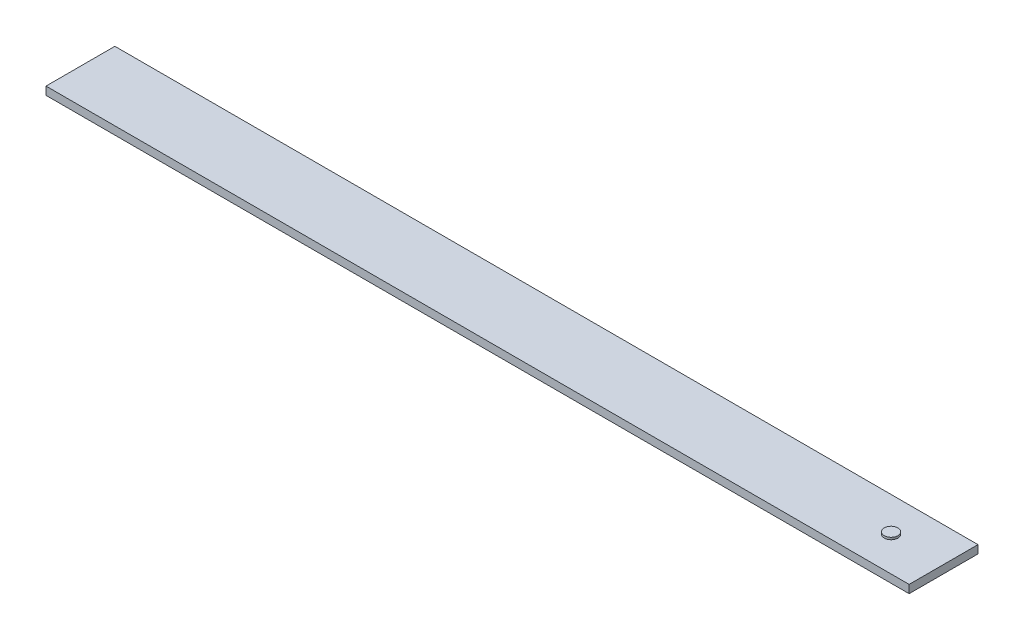
SolidWorks part; units mm, degrees
ref_plane "Plano frontal" through (0, 0, 0) normal (0, 0, 1) x (1, 0, 0)
ref_plane "Plano superior" through (0, 0, 0) normal (0, 1, 0) x (1, 0, 0)
ref_plane "Plano direito" through (0, 0, 0) normal (1, 0, 0) x (0, 0, -1)
sketch "Esboço1" plane through (0, 0, 0) normal (0, 1, 0) x (1, 0, 0)
  line L1 (0, 0) -> (401, 0)
  line L2 (0, 0) -> (0, 32)
  line L3 (0, 32) -> (401, 32)
  line L4 (401, 0) -> (401, 32)
extrude "Ressalto-extrusão1" add sketch "Esboço1" along normal blind 3.75
sketch "Esboço6" plane through (0, 3.75, 0) normal (0, 1, 0) x (1, 0, 0)
  circle A0 centre (376.65, 16) radius 3.15
extrude "Ressalto-extrusão3" add sketch "Esboço6" along normal blind 1
